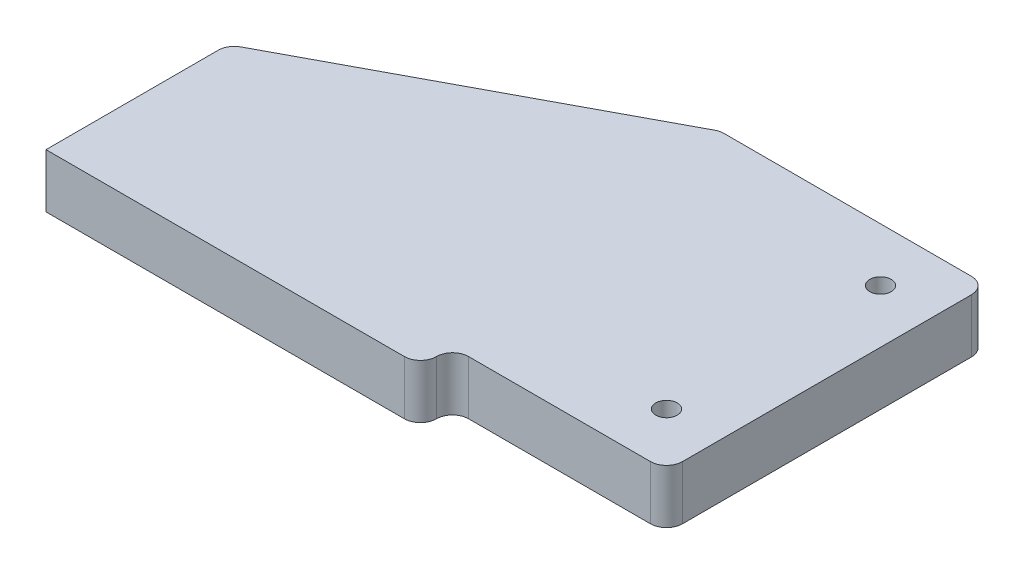
SolidWorks part; units mm, degrees
ref_plane "Front Plane" through (0, 0, 0) normal (0, 0, 1) x (1, 0, 0)
ref_plane "Top Plane" through (0, 0, 0) normal (0, 1, 0) x (1, 0, 0)
ref_plane "Right Plane" through (0, 0, 0) normal (1, 0, 0) x (0, 0, -1)
sketch "Sketch1" plane through (0, 0, 0) normal (0, 1, 0) x (1, 0, 0)
  line L0 (1.905, 0) -> (23.495, 0)
  line L1 (25.4, 1.905) -> (25.4, 36.195)
  line L2 (23.495, 38.1) -> (-5.8737, 38.1)
  line L3 (-6.7702, 37.8759) -> (-43.4415, 18.3179)
  line L4 (-44.45, 16.637) -> (-44.45, -3.81)
  line L5 (-44.45, -3.81) -> (-1.905, -3.81)
  arc A0 (-1.905, -3.81) -> (0, -1.905) centre (-1.905, -1.905) ccw
  circle A1 centre (19.05, 31.75) radius 1.27
  circle A2 centre (19.05, 6.35) radius 1.27
  arc A3 (25.4, 36.195) -> (23.495, 38.1) centre (23.495, 36.195) ccw
  arc A4 (-43.4415, 18.3179) -> (-44.45, 16.637) centre (-42.545, 16.637) ccw
  arc A5 (-5.8737, 38.1) -> (-6.7702, 37.8759) centre (-5.8737, 36.195) ccw
  arc A6 (1.905, 0) -> (0, -1.905) centre (1.905, -1.905) ccw
  arc A7 (23.495, 0) -> (25.4, 1.905) centre (23.495, 1.905) ccw
  dimension "D6" = 3.81
  dimension "D8" = 3.81
  dimension "D2" = 25.4
  dimension "D9" = 3.81
  dimension "D10" = 3.81
  dimension "D11" = 25.4
  dimension "D12" = 1.905
  dimension "D13" = 2.54
  dimension "D14" = 2.54
  dimension "D15" = 6.35
  dimension "D3" = 6.35
  dimension "D4" = 38.1
  dimension "D5" = 44.45
  dimension "D7" = 3.81
extrude "Boss-Extrude1" add sketch "Sketch1" along normal blind 6.4008
